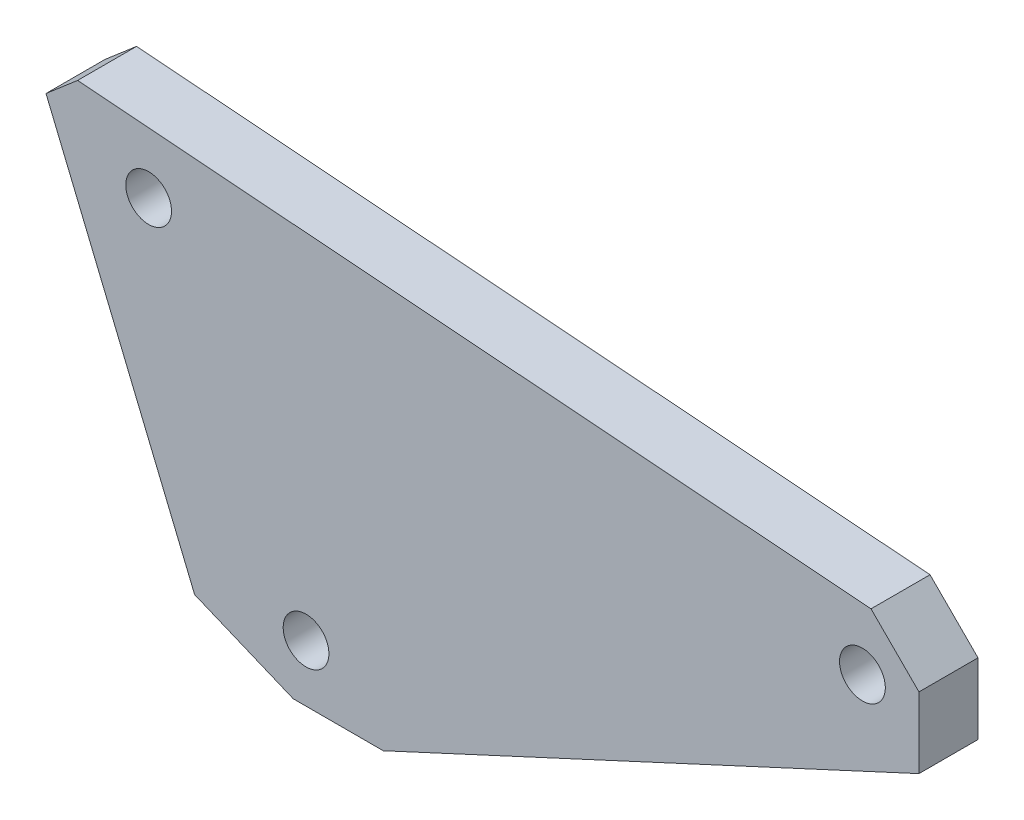
SolidWorks part; units mm, degrees
ref_plane "Plan de face" through (0, 0, 0) normal (0, 0, 1) x (1, 0, 0)
ref_plane "Plan de dessus" through (0, 0, 0) normal (0, 1, 0) x (1, 0, 0)
ref_plane "Plan de droite" through (0, 0, 0) normal (1, 0, 0) x (0, 0, -1)
sketch "Esquisse1" plane through (0, 0, 0) normal (0, 0, 1) x (1, 0, 0)
  line L0 (-19.6947, 14.1252) -> (-7.6254, -15.0803)
  line L1 (-7.6254, -15.0803) -> (4.0073, -15.0803)
  line L2 (4.0073, -15.0803) -> (40.3053, 1.7262)
  line L3 (40.3053, 1.7262) -> (40.3053, 9.5225)
  line L4 (40.3053, 9.5225) -> (-19.6947, 14.1252)
  dimension "D1" = 60
  dimension "D2" = 29.2055
  dimension "D3" = 40
  dimension "D4" = 7.7964
  dimension "D5" = 11.6327
extrude "Boss.-Extru.1" add sketch "Esquisse1" along normal blind 4
sketch "Esquisse2" plane through (0, 0, 4) normal (0, 0, 1) x (1, 0, 0)
  circle A0 centre (-11.8878, 9.4029) radius 1.55
  circle A1 centre (-1.2227, -11.2287) radius 1.55
  circle A2 centre (36.4749, 5.6244) radius 1.55
  dimension "D1" = 3.1
extrude "Enlèv. mat.-Extru.1" cut sketch "Esquisse2" against normal blind 7 and the other way blind 4
chamfer "Chanfrein1" distance 3 angle 45 3 edges at (-19.6947, 14.1252, 2) (-7.6254, -15.0803, 2) (40.3053, 9.5225, 2)
